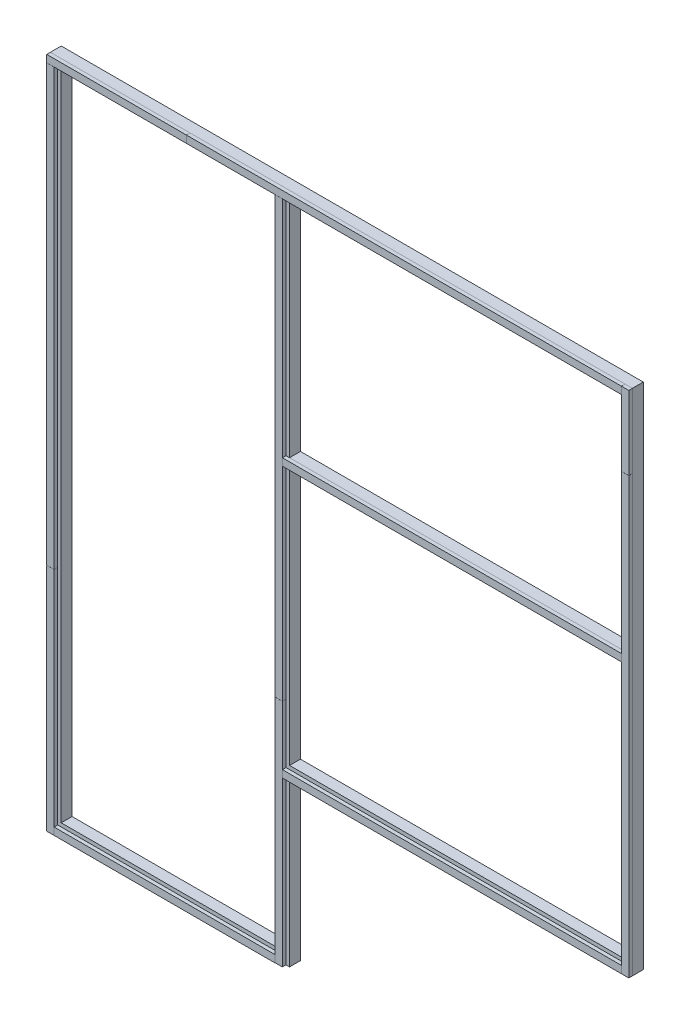
SolidWorks part; units mm, degrees
ref_plane "Спереди" through (0, 0, 0) normal (0, 0, 1) x (1, 0, 0)
ref_plane "Сверху" through (0, 0, 0) normal (0, 1, 0) x (1, 0, 0)
ref_plane "Справа" through (0, 0, 0) normal (1, 0, 0) x (0, 0, -1)
sketch "Эскиз1" plane through (0, 0, 0) normal (0, 0, 1) x (1, 0, 0)
  line L0 (50, -50) -> (8077, -50)
  line L1 (8077, -50) -> (8077, -7068)
  line L2 (8077, -7068) -> (3349, -7068)
  line L3 (3349, -6915) -> (3349, -7121) construction
  line L4 (3349, -7068) -> (3349, -9325)
  line L5 (3349, -9325) -> (50, -9328)
  line L6 (50, -9328) -> (50, -50)
  line L7 (200, -200) -> (3199, -200)
  line L8 (203, -200) -> (3965, -200) construction
  line L9 (3199, -200) -> (3199, -9178)
  line L10 (3199, -9178) -> (200, -9178)
  line L11 (200, -9178) -> (200, -200)
  line L12 (7927, -200) -> (7927, -3243)
  line L13 (7927, -203) -> (7927, -6918) construction
  line L14 (7927, -3243) -> (3349, -3243)
  line L15 (7184, -3243) -> (3199, -3243) construction
  line L16 (3349, -3243) -> (3349, -200)
  line L17 (3349, -200) -> (7927, -200)
  line L18 (7927, -6918) -> (7927, -3393)
  line L19 (7927, -3393) -> (3349, -3393)
  line L20 (3199, -3393) -> (7184, -3393) construction
  line L21 (3349, -3393) -> (3349, -6918)
  line L22 (3349, -6918) -> (7927, -6918)
  dimension "D1" = 150
extrude "Бобышка-Вытянуть1" add sketch "Эскиз1" along normal blind 150
sketch "Эскиз2" plane through (0, 0, 150) normal (0, 0, 1) x (1, 0, 0)
  line L0 (8077, -50) -> (50, -50) construction
  line L1 (8077, -7068) -> (7977, -7068)
  line L2 (8077, -7068) -> (8077, -1068)
  line L3 (8077, -1068) -> (7977, -1068)
  line L4 (7977, -7068) -> (7977, -1068)
  line L5 (8077, -50) -> (7977, -50)
  line L6 (8077, -50) -> (8077, -1067)
  line L7 (8077, -1067) -> (7977, -1067)
  line L8 (7977, -50) -> (7977, -1067)
  line L9 (7976, -50) -> (1976, -50)
  line L10 (7976, -50) -> (7976, -150)
  line L11 (7976, -150) -> (1976, -150)
  line L12 (1976, -50) -> (1976, -150)
  line L13 (50, -50) -> (50, -9328) construction
  line L14 (1975, -50) -> (50, -50)
  line L15 (1975, -50) -> (1975, -150)
  line L16 (1975, -150) -> (50, -150)
  line L17 (50, -50) -> (50, -150)
  line L18 (3199, -9178) -> (3199, -200) construction
  line L19 (50, -151) -> (150, -151)
  line L20 (50, -151) -> (50, -6151)
  line L21 (50, -6151) -> (150, -6151)
  line L22 (150, -151) -> (150, -6151)
  line L23 (3199, -151) -> (3299, -151)
  line L24 (3199, -151) -> (3199, -6151)
  line L25 (3199, -6151) -> (3299, -6151)
  line L26 (3299, -151) -> (3299, -6151)
  line L27 (50, -9328) -> (3349, -9325) construction
  line L28 (3199, -6152) -> (3299, -6152)
  line L29 (3199, -6152) -> (3199, -9325.0455)
  line L30 (3199, -9325.0455) -> (3299, -9325.0455)
  line L31 (3299, -6152) -> (3299, -9325.0455)
  line L32 (3349, -7068) -> (8077, -7068) construction
  line L33 (50, -6152) -> (150, -6152)
  line L34 (50, -6152) -> (50, -9327.9091)
  line L35 (50, -9327.9091) -> (150, -9327.9091)
  line L36 (150, -6152) -> (150, -9327.9091)
  line L37 (151, -9327.9082) -> (3198, -9327.9082)
  line L38 (151, -9327.9082) -> (151, -9227.9082)
  line L39 (151, -9227.9082) -> (3198, -9227.9082)
  line L40 (3198, -9327.9082) -> (3198, -9227.9082)
  line L41 (3300, -7068) -> (7976, -7068)
  line L42 (3300, -7068) -> (3300, -6968)
  line L43 (3300, -6968) -> (7976, -6968)
  line L44 (7976, -7068) -> (7976, -6968)
  line L45 (3349, -3243) -> (7927, -3243) construction
  line L46 (3300, -3243) -> (7976, -3243)
  line L47 (3300, -3243) -> (3300, -3343)
  line L48 (3300, -3343) -> (7976, -3343)
  line L49 (7976, -3243) -> (7976, -3343)
  dimension "D1" = 100
  dimension "D2" = 6000
  dimension "D3" = 1
  dimension "D4" = 1017
  dimension "D5" = 1
  dimension "D6" = 6000
  dimension "D7" = 1
  dimension "D8" = 1
  dimension "D9" = 1
  dimension "D10" = 100
  dimension "D11" = 6000
  dimension "D12" = 3173.0455
  dimension "D13" = 6000
  dimension "D14" = 100
  dimension "D15" = 1
  dimension "D16" = 1
  dimension "D17" = 100
  dimension "D18" = 1
  dimension "D19" = 1
  dimension "D20" = 100
  dimension "D21" = 1
  dimension "D22" = 1
  dimension "D23" = 1
  dimension "D24" = 100
  dimension "D25" = 1
extrude "Бобышка-Вытянуть2" add sketch "Эскиз2" along normal blind 50 separate body
